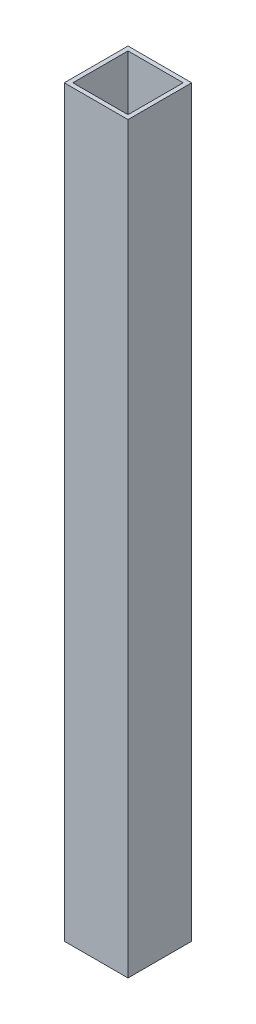
SolidWorks part; units mm, degrees
material "ABS"
ref_plane "Alzado" through (0, 0, 0) normal (0, 0, 1) x (1, 0, 0)
ref_plane "Planta" through (0, 0, 0) normal (0, 1, 0) x (1, 0, 0)
ref_plane "Vista lateral" through (0, 0, 0) normal (1, 0, 0) x (0, 0, -1)
sketch "Sketch1" plane through (0, 0, 0) normal (0, 1, 0) x (1, 0, 0)
  line L1 (-7.5, -7.5) -> (7.5, -7.5)
  line L2 (-7.5, -7.5) -> (-7.5, 7.5)
  line L3 (-7.5, 7.5) -> (7.5, 7.5)
  line L4 (7.5, -7.5) -> (7.5, 7.5)
  line L5 (-7.5, -7.5) -> (7.5, 7.5) construction
  line L6 (-7.5, 7.5) -> (7.5, -7.5) construction
  line L7 (-6.5, -6.5) -> (6.5, -6.5)
  line L8 (-6.5, -6.5) -> (-6.5, 6.5)
  line L9 (-6.5, 6.5) -> (6.5, 6.5)
  line L10 (6.5, -6.5) -> (6.5, 6.5)
  line L11 (-6.5, -6.5) -> (6.5, 6.5) construction
  line L12 (-6.5, 6.5) -> (6.5, -6.5) construction
  point P0 (0, 0)
  point P6 (0, 0)
  dimension "D1" = 15
  dimension "D2" = 13
extrude "Boss-Extrude1" add sketch "Sketch1" along normal blind 175
